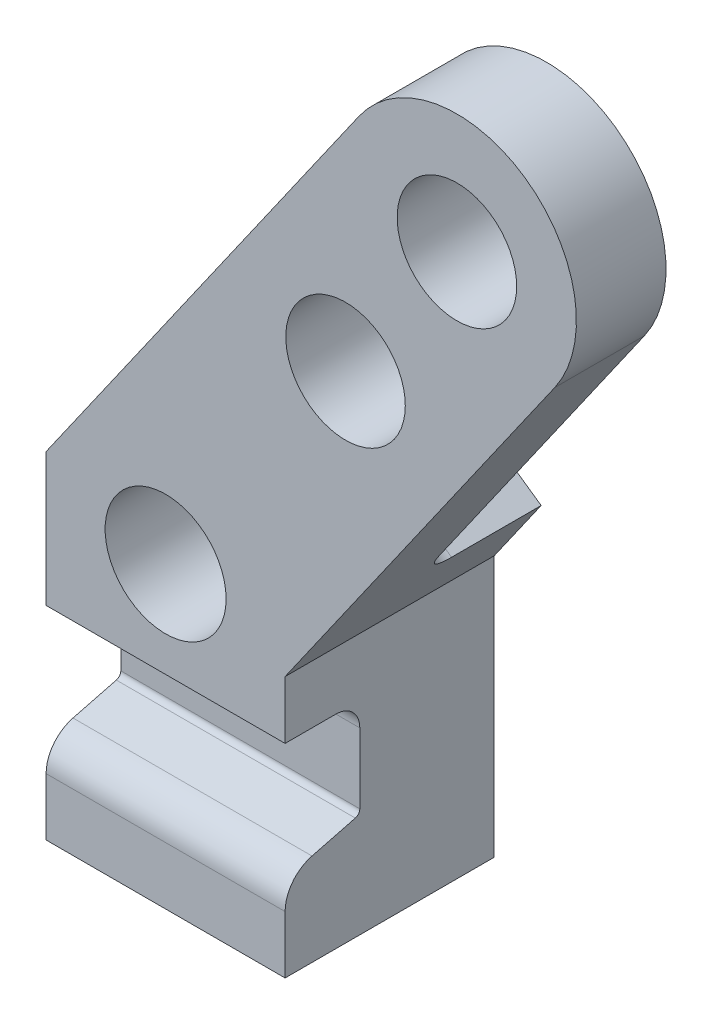
SolidWorks part; units mm, degrees
ref_plane "前视基准面" through (0, 0, 0) normal (0, 0, 1) x (1, 0, 0)
ref_plane "上视基准面" through (0, 0, 0) normal (0, 1, 0) x (1, 0, 0)
ref_plane "右视基准面" through (0, 0, 0) normal (1, 0, 0) x (0, 0, -1)
sketch "草图1" plane through (0, 0, 0) normal (0, 0, 1) x (1, 0, 0)
  line L0 (0, -1000) -> (0, 49000) construction
  line L1 (0, 0) -> (28678.8218, 40957.6022) construction
  line L2 (-1000, 0) -> (49000, 0) construction
  line L3 (64.7419, 162.1989) -> (-40, 12.612)
  line L4 (130.2741, 116.3128) -> (40, -12.612)
  line L5 (-40, 12.612) -> (-40, -100)
  line L6 (-40, -100) -> (40, -100)
  line L7 (40, -100) -> (40, -12.612)
  circle A0 centre (0, 0) radius 20.25
  circle A1 centre (97.508, 139.2558) radius 20
  circle A2 centre (60.2255, 86.011) radius 20
  arc A3 (64.7419, 162.1989) -> (130.2741, 116.3128) centre (97.508, 139.2558) cw
  dimension "D2" = 40.5
  dimension "D3" = 40
  dimension "D4" = 40
  dimension "D7" = 40
  dimension "D1" = 55
  dimension "D5" = 105
  dimension "D6" = 170
  dimension "D8" = 40
  dimension "D9" = 40
  dimension "D10" = 100
extrude "凸台-拉伸1" add sketch "草图1" along normal blind 70
sketch "草图2" plane through (0, 0, 0) normal (0, 0, 1) x (1, 0, 0)
  line L0 (-9.823, 55.7091) -> (55.7091, 9.823)
  line L1 (64.7419, 162.1989) -> (-40, 12.612) construction
  line L2 (40, -12.612) -> (130.2741, 116.3128) construction
  line L3 (55.7091, 9.823) -> (170.4244, 173.6534)
  line L4 (170.4244, 173.6534) -> (104.8923, 219.5395)
  line L5 (104.8923, 219.5395) -> (-9.823, 55.7091)
  circle A0 centre (97.508, 139.2558) radius 20 construction
  dimension "D1" = 130
  dimension "D2" = 200
extrude "切除-拉伸1" cut sketch "草图2" along normal blind 40
sketch "草图3" plane through (-40, 0, 0) normal (-1, 0, 0) x (0, 0, 1)
  line L0 (70, -32) -> (45, -32)
  line L1 (70, 12.612) -> (70, -100) construction
  line L2 (45, -32) -> (45, -65)
  line L3 (45, -65) -> (70, -71.455)
  line L4 (70, -71.455) -> (70, -32)
  line L5 (45, -65) -> (122.4597, -65) construction
  line L6 (45, -65) -> (122.4597, -85) construction
  dimension "D1" = 32
  dimension "D2" = 33
  dimension "D3" = 25
  dimension "D4" = 20
  dimension "D5" = 80
extrude "切除-拉伸2" cut sketch "草图3" against normal through all
fillet "圆角1" radius 12 1 edges at (0, -71.455, 70)
fillet "圆角2" radius 2 1 edges at (0, -65, 45)
fillet "圆角3" radius 8 1 edges at (0, -32, 45)
fillet "圆角4" radius 10 1 edges at (22.9431, 32.7661, 40)
